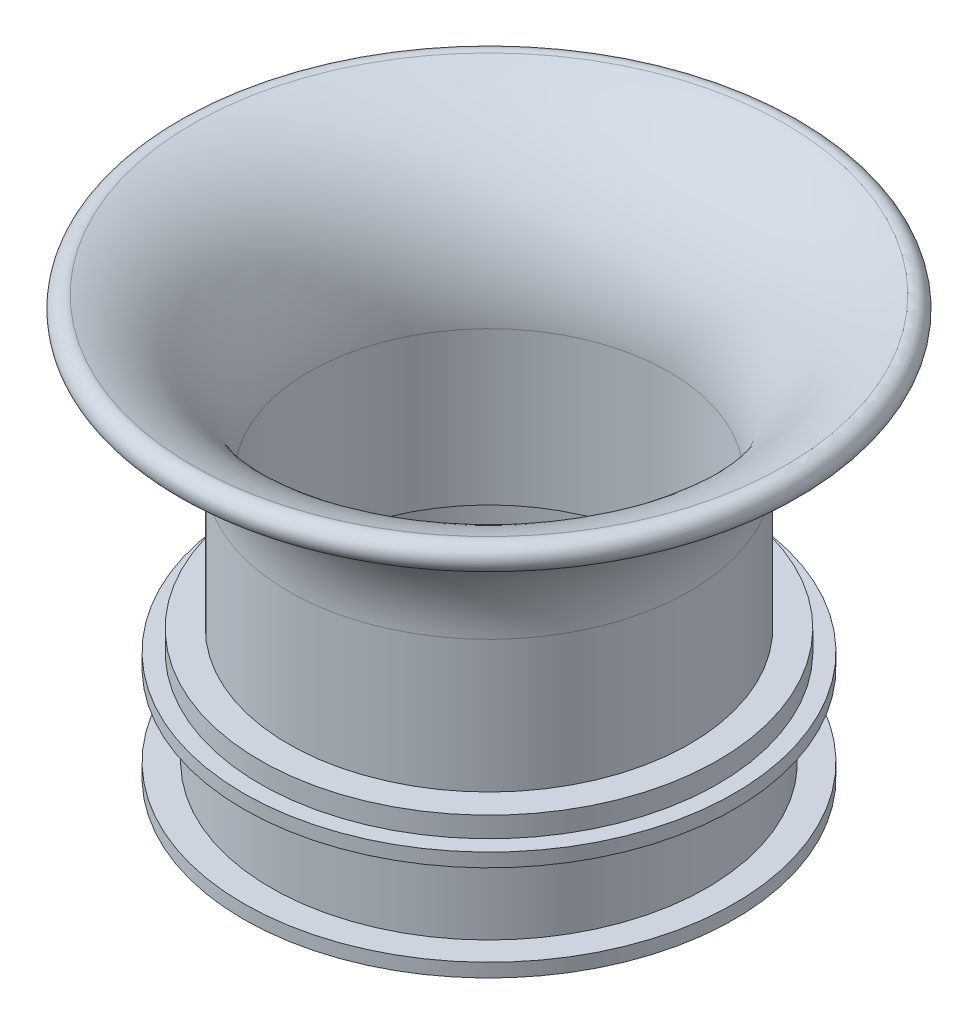
SolidWorks part; units mm, degrees
material "6063-T1"
ref_plane "Front Plane" through (0, 0, 0) normal (0, 0, 1) x (1, 0, 0)
ref_plane "Top Plane" through (0, 0, 0) normal (0, 1, 0) x (1, 0, 0)
ref_plane "Right Plane" through (0, 0, 0) normal (1, 0, 0) x (0, 0, -1)
sketch "Sketch2" plane through (0, 0, 0) normal (0, 0, 1) x (1, 0, 0)
  line L0 (0, 0) -> (0, 64.8372) construction
  line L1 (20.955, 30.48) -> (20.955, 12.7)
  line L2 (23.368, 30.48) -> (23.368, 15.0792)
  line L3 (23.368, 15.0792) -> (26.67, 15.0792)
  line L4 (26.67, 15.0792) -> (26.67, 12.7)
  line L5 (26.67, 12.7) -> (28.575, 12.7)
  line L6 (28.575, 12.7) -> (28.575, 11.1125)
  line L7 (28.575, 11.1125) -> (25.4, 11.1125)
  line L8 (25.4, 11.1125) -> (25.4, 1.5875)
  line L9 (20.955, 12.7) -> (22.225, 12.7)
  line L10 (22.225, 12.7) -> (22.225, 0)
  line L11 (25.4, 1.5875) -> (28.575, 1.5875)
  line L12 (28.575, 1.5875) -> (28.575, 0)
  line L13 (28.575, 0) -> (22.225, 0)
  arc A0 (20.955, 30.48) -> (34.4955, 48.7159) centre (40.005, 30.48) cw
  arc A1 (35.2944, 45.8561) -> (34.4955, 48.7159) centre (34.925, 47.2944) ccw
  arc A2 (23.368, 30.48) -> (35.2944, 45.8561) centre (39.243, 30.48) cw
  dimension "D12" = 19.05
  dimension "D13" = 15.875
  dimension "D1" = 20.955
  dimension "D2" = 22.225
  dimension "D3" = 12.7
  dimension "D4" = 17.78
  dimension "D5" = 1.5875
  dimension "D6" = 1.5875
  dimension "D7" = 9.525
  dimension "D8" = 3.175
  dimension "D9" = 6.35
  dimension "D10" = 1.905
  dimension "D11" = 2.413
  dimension "D14" = 34.925
revolve "Revolve1" add sketch "Sketch2" angle 360 about L0
